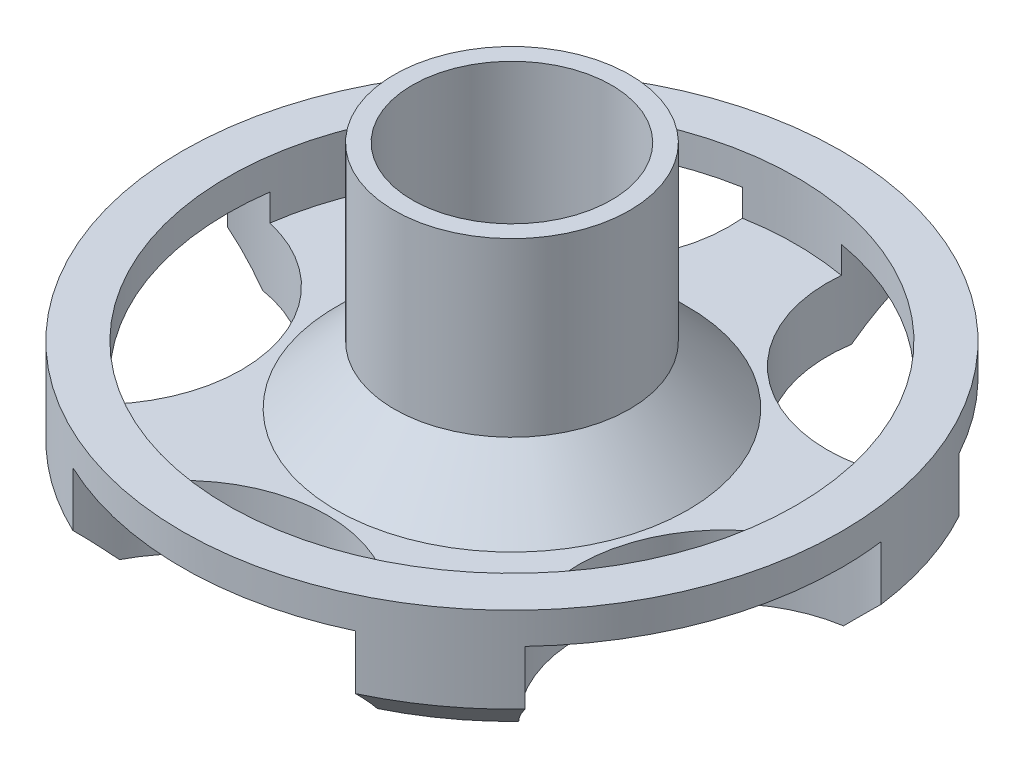
SolidWorks part; units mm, degrees
ref_plane "Front Plane" through (0, 0, 0) normal (0, 0, 1) x (1, 0, 0)
ref_plane "Top Plane" through (0, 0, 0) normal (0, 1, 0) x (1, 0, 0)
ref_plane "Right Plane" through (0, 0, 0) normal (1, 0, 0) x (0, 0, -1)
sketch "Sketch2" plane through (0, 0, 0) normal (0, 0, 1) x (1, 0, 0)
  line L0 (10.9359, 19) -> (-2.0641, 19)
  line L1 (-2.0641, 19) -> (-2.0641, 0)
  line L5 (-20.4641, 0) -> (-25.4641, 0)
  line L6 (-25.4641, 0) -> (-25.4641, -9.4624)
  line L7 (-21.4641, -13.4624) -> (10.9359, -13.4624)
  line L8 (10.9359, -13.4624) -> (10.9359, 19)
  line L11 (-20.4641, 0) -> (-20.4641, -6.4315)
  line L13 (-20.4641, -6.4315) -> (-8.4955, -6.4315)
  line L14 (-2.0641, 0) -> (-8.4955, -6.4315)
  line L15 (-25.4641, -9.4624) -> (-21.4641, -13.4624)
  point P9 (-25.4641, -13.4624)
  dimension "D1" = 13
  dimension "D2" = 19
  dimension "D3" = 36.4
  dimension "D4" = 5
  dimension "D5" = 135
  dimension "D6" = 10.9359
  dimension "D7" = 8.4955
  dimension "D8" = 13.4624
revolve "Revolve1" add sketch "Sketch2" angle 360 about L8
sketch "Sketch3" plane through (0, 19, 0) normal (0, 1, 0) x (1, 0, 0)
  circle A0 centre (10.9359, 0) radius 11
  dimension "D1" = 22
extrude "Cut-Extrude1" cut sketch "Sketch3" against normal up to next
sketch "Sketch4" plane through (0, -13.4624, 0) normal (0, -1, 0) x (1, 0, 0)
  line L0 (10.9359, 0) -> (10.9359, 36.4) construction
  circle A0 centre (10.9359, 0) radius 36.4 construction
  circle A1 centre (10.9359, 36.4) radius 16
  circle A2 centre (45.5544, 11.2482) radius 16
  circle A3 centre (32.3313, -29.4482) radius 16
  circle A4 centre (-10.4594, -29.4482) radius 16
  circle A5 centre (-23.6825, 11.2482) radius 16
  point P18 (10.9359, 0)
  dimension "D1" = 32
  dimension "D2" = 5
extrude "Cut-Extrude2" cut sketch "Sketch4" against normal blind 10
